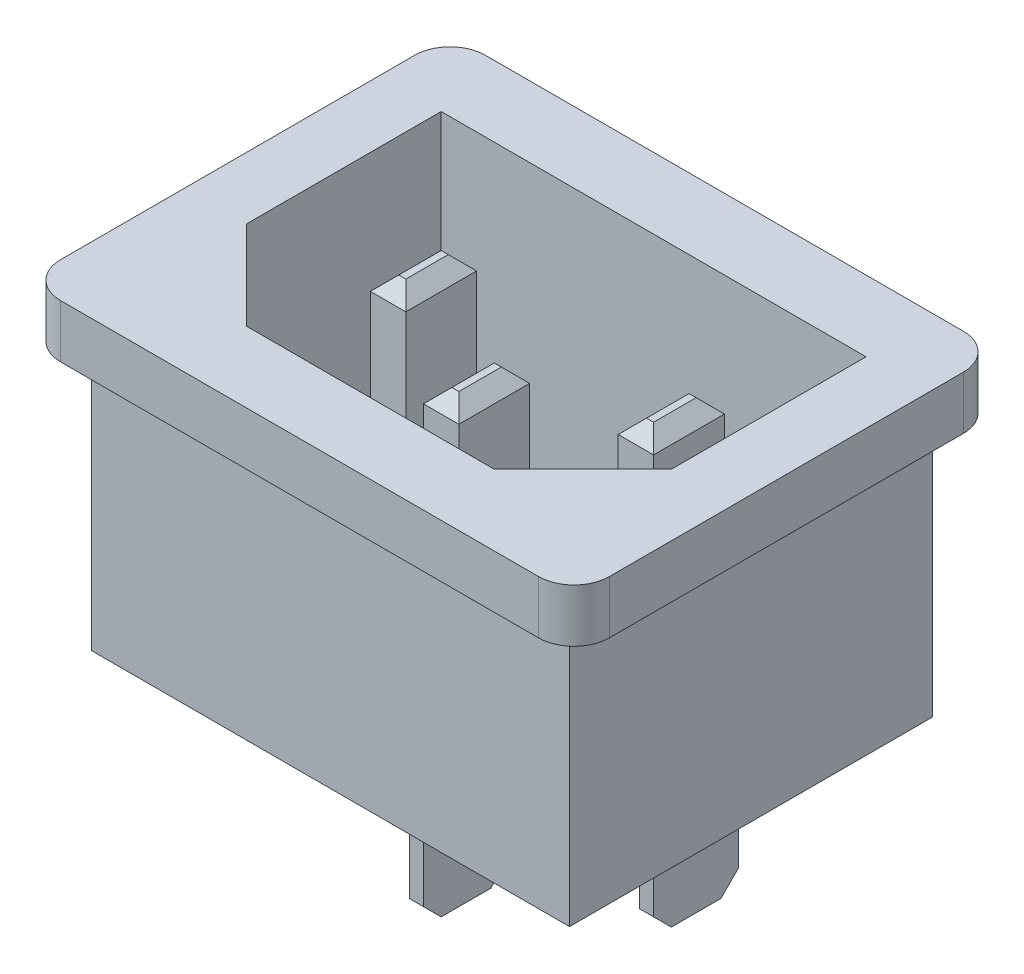
SolidWorks part; units mm, degrees
ref_plane "Спереди" through (0, 0, 0) normal (0, 0, 1) x (1, 0, 0)
ref_plane "Сверху" through (0, 0, 0) normal (0, 1, 0) x (1, 0, 0)
ref_plane "Справа" through (0, 0, 0) normal (1, 0, 0) x (0, 0, -1)
sketch "Эскиз1" plane through (0, 0, 0) normal (0, 1, 0) x (1, 0, 0)
  line L1 (-13.5, -10.25) -> (13.5, -10.25)
  line L2 (-13.5, -10.25) -> (-13.5, 10.25)
  line L3 (-13.5, 10.25) -> (13.5, 10.25)
  line L4 (13.5, -10.25) -> (13.5, 10.25)
  line L5 (-13.5, -10.25) -> (13.5, 10.25) construction
  line L6 (-13.5, 10.25) -> (13.5, -10.25) construction
  point P0 (0, 0)
  dimension "D1" = 20.5
  dimension "D2" = 27
extrude "Бобышка-Вытянуть1" add sketch "Эскиз1" along normal blind 15
sketch "Эскиз2" plane through (0, 0, 0) normal (0, -1, 0) x (1, 0, 0)
  line L0 (0.4, 0.6) -> (0.4, 5.4)
  line L1 (-7.4, -5.4) -> (-6.6, -5.4)
  line L2 (-7.4, -5.4) -> (-7.4, -0.6)
  line L3 (-7.4, -0.6) -> (-6.6, -0.6)
  line L4 (-6.6, -5.4) -> (-6.6, -0.6)
  line L5 (-7.4, -5.4) -> (-6.6, -0.6) construction
  line L6 (-7.4, -0.6) -> (-6.6, -5.4) construction
  line L7 (-0.4, 0.6) -> (-0.4, 5.4)
  line L8 (-0.4, 5.4) -> (0.4, 5.4)
  line L9 (-0.4, 0.6) -> (0.4, 5.4) construction
  line L10 (-0.4, 0.6) -> (0.4, 0.6)
  line L11 (-0.4, 5.4) -> (0.4, 0.6) construction
  line L12 (6.6, -0.6) -> (7.4, -0.6)
  line L13 (6.6, -5.4) -> (7.4, -5.4)
  line L14 (6.6, -5.4) -> (6.6, -0.6)
  line L15 (6.6, -5.4) -> (7.4, -0.6) construction
  line L16 (6.6, -0.6) -> (7.4, -5.4) construction
  line L17 (7.4, -5.4) -> (7.4, -0.6)
  point P0 (-7, -3)
  point P5 (0, 3)
  point P10 (7, -3)
  dimension "D1" = 0.8
  dimension "D2" = 4.8
  dimension "D3" = 0.8
  dimension "D4" = 4.8
  dimension "D5" = 0.8
  dimension "D6" = 4.8
  dimension "D7" = 14
  dimension "D8" = 7
  dimension "D9" = 6
  dimension "D10" = 3
extrude "Бобышка-Вытянуть2" add sketch "Эскиз2" along normal blind 9
chamfer "Фаска1" distance 1 angle 45 6 edges at (7, -9, -5.4) (7, -9, -0.6) (-7, -9, -5.4) (-7, -9, -0.6) (0, -9, 0.6) (0, -9, 5.4)
sketch "Эскиз3" plane through (0, 15, 0) normal (0, 1, 0) x (1, 0, 0)
  line L1 (15.5, 12) -> (-15.5, 12)
  line L2 (15.5, 12) -> (15.5, -12)
  line L3 (15.5, -12) -> (-15.5, -12)
  line L4 (-15.5, 12) -> (-15.5, -12)
  line L5 (15.5, 12) -> (-15.5, -12) construction
  line L6 (15.5, -12) -> (-15.5, 12) construction
  point P0 (0, 0)
  dimension "D1" = 24
  dimension "D2" = 31
extrude "Бобышка-Вытянуть3" add sketch "Эскиз3" along normal blind 3
sketch "Эскиз4" plane through (0, 18, 0) normal (0, 1, 0) x (1, 0, 0)
  line L0 (12, -3) -> (7, -8)
  line L1 (12, 8) -> (-12, 8)
  line L2 (12, 8) -> (12, -3)
  line L3 (7, -8) -> (-7, -8)
  line L4 (-12, 8) -> (-12, -3)
  line L5 (12, 8) -> (-12, -8) construction
  line L6 (12, -8) -> (-12, 8) construction
  line L7 (-7, -8) -> (-12, -3)
  point P0 (0, 0)
  dimension "D1" = 24
  dimension "D2" = 16
extrude "Вырез-Вытянуть1" cut sketch "Эскиз4" against normal blind 17
sketch "Эскиз5" plane through (0, 1, 0) normal (0, 1, 0) x (1, 0, 0)
  line L0 (8, 0) -> (8, 4)
  line L1 (1, -4) -> (-1, -4)
  line L2 (1, -4) -> (1, 0)
  line L3 (1, 0) -> (-1, 0)
  line L4 (-1, -4) -> (-1, 0)
  line L5 (1, -4) -> (-1, 0) construction
  line L6 (1, 0) -> (-1, -4) construction
  line L7 (8, 4) -> (6, 0) construction
  line L8 (8, 0) -> (6, 4) construction
  line L9 (8, 0) -> (6, 0)
  line L10 (8, 4) -> (6, 4)
  line L11 (6, 0) -> (6, 4)
  line L12 (-6, 0) -> (-8, 4) construction
  line L13 (-6, 4) -> (-8, 0) construction
  line L14 (-8, 0) -> (-8, 4)
  line L15 (-6, 4) -> (-8, 4)
  line L16 (-6, 0) -> (-6, 4)
  line L17 (-6, 0) -> (-8, 0)
  point P0 (0, -2)
  point P5 (7, 2)
  point P11 (-7, 2)
  dimension "D1" = 2
  dimension "D2" = 4
  dimension "D3" = 2
  dimension "D4" = 4
  dimension "D5" = 2
  dimension "D6" = 4
  dimension "D7" = 4
  dimension "D8" = 2
  dimension "D9" = 7
  dimension "D10" = 14
extrude "Бобышка-Вытянуть4" add sketch "Эскиз5" along normal blind 15
chamfer "Фаска2" distance 0.8 angle 45 12 edges at (0, 16, 0) (1, 16, 2) (0, 16, 4) (-1, 16, 2) (-6, 16, -2) (-7, 16, 0) (-8, 16, -2) (-7, 16, -4) (7, 16, -4) (8, 16, -2) (6, 16, -2) (7, 16, 0)
fillet "Скругление1" radius 2 4 edges at (15.5, 16.5, -12) (15.5, 16.5, 12) (-15.5, 16.5, -12) (-15.5, 16.5, 12)
